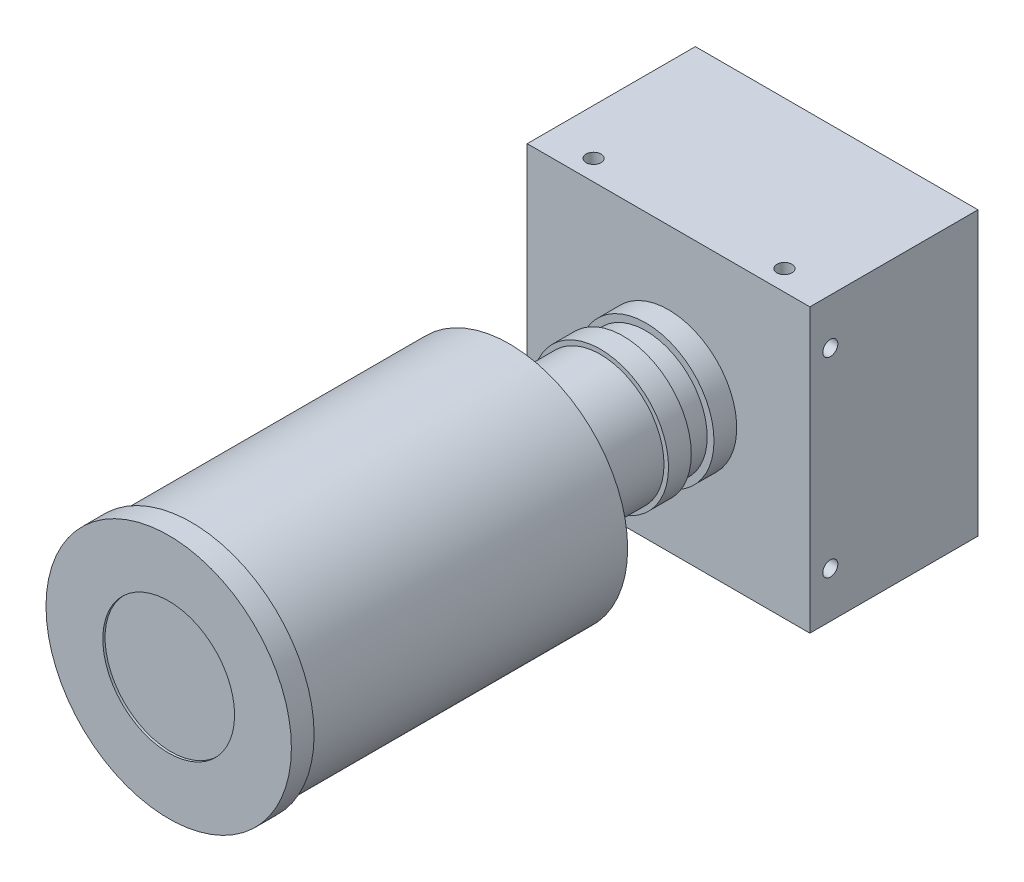
SolidWorks part; units mm, degrees
material "铝合金 (2)"
ref_plane "前基準面" through (0, 0, 0) normal (0, 0, 1) x (1, 0, 0)
ref_plane "上基準面" through (0, 0, 0) normal (0, 1, 0) x (1, 0, 0)
ref_plane "右基準面" through (0, 0, 0) normal (1, 0, 0) x (0, 0, -1)
sketch "草图1" plane through (0, 0, 0) normal (0, 0, 1) x (1, 0, 0)
  line L1 (0, 0) -> (62.2, 0)
  line L2 (0, 0) -> (0, 62.2)
  line L3 (0, 62.2) -> (62.2, 62.2)
  line L4 (62.2, 0) -> (62.2, 62.2)
  dimension "D1" = 62.2
extrude "凸台-拉伸1" add sketch "草图1" along normal blind 37
sketch "草图2" plane through (0, 0, 37) normal (0, 0, 1) x (1, 0, 0)
  line L0 (31.1, 62.2) -> (31.1, 0) construction
  line L1 (62.2, 62.2) -> (0, 62.2) construction
  line L2 (0, 0) -> (62.2, 0) construction
  circle A0 centre (31.1, 31.1) radius 15
  dimension "D1" = 30
extrude "凸台-拉伸2" add sketch "草图2" along normal blind 5
sketch "草图3" plane through (0, 0, 42) normal (0, 0, 1) x (1, 0, 0)
  circle A0 centre (31.1, 31.1) radius 13.5
  dimension "D1" = 27
extrude "凸台-拉伸3" add sketch "草图3" along normal blind 5
sketch "草图4" plane through (0, 0, 47) normal (0, 0, 1) x (1, 0, 0)
  circle A0 centre (31.1, 31.1) radius 15
  dimension "D1" = 30
extrude "凸台-拉伸4" add sketch "草图4" along normal blind 5
sketch "草图5" plane through (0, 0, 52) normal (0, 0, 1) x (1, 0, 0)
  circle A0 centre (31.1, 31.1) radius 14
  dimension "D1" = 28
extrude "凸台-拉伸5" add sketch "草图5" along normal blind 20
sketch "草图6" plane through (0, 0, 72) normal (0, 0, 1) x (1, 0, 0)
  circle A0 centre (31.1, 31.1) radius 26
  dimension "D1" = 52
extrude "凸台-拉伸6" add sketch "草图6" along normal blind 70
sketch "草图7" plane through (0, 0, 142) normal (0, 0, 1) x (1, 0, 0)
  circle A0 centre (31.1, 31.1) radius 27
  dimension "D1" = 54
extrude "凸台-拉伸7" add sketch "草图7" along normal blind 5
sketch "草图8" plane through (0, 0, 147) normal (0, 0, 1) x (1, 0, 0)
  circle A0 centre (31.1, 31.1) radius 14.5
  dimension "D1" = 29
extrude "切除-拉伸1" cut sketch "草图8" against normal blind 0.5
sketch "草图9" plane through (0, 0, 0) normal (0, 0, -1) x (-1, 0, 0)
  circle A0 centre (-16.5763, 47.3033) radius 3.4696
  circle A1 centre (-16.5763, 47.3033) radius 4.9876
extrude "凸台-拉伸8" add sketch "草图9" along normal blind 7
sketch "草图10" plane through (0, 0, 0) normal (0, 0, -1) x (-1, 0, 0)
  line L1 (-24.6285, 18.2507) -> (-16.4054, 18.2507)
  line L2 (-24.6285, 18.2507) -> (-24.6285, 13.1265)
  line L3 (-24.6285, 13.1265) -> (-16.4054, 13.1265)
  line L4 (-16.4054, 18.2507) -> (-16.4054, 13.1265)
extrude "切除-拉伸2" cut sketch "草图10" against normal blind 3
hole_wizard "M4 螺纹孔1" positions "草图12" profile "草图11" tap size "M4" standard "ISO"
sketch "草图12" plane through (0, 62.2, 0) normal (0, 1, 0) x (-1, 0, 0)
  line L0 (-31.1, 37) -> (-31.1, 20.8859) construction
  line L1 (-62.2, 37) -> (0, 37) construction
  point P0 (-10.1, 32.5)
  point P1 (-52.1, 32.5)
  dimension "D1" = 42
  dimension "D2" = 4.5
sketch "草图11" plane through (10.1, 62.2, 32.5) normal (1, 0, 0) x (0, 0, 1)
  line L0 (0, 0) -> (0, 11.0914)
  line L1 (0, 11.0914) -> (1.65, 10.1)
  line L2 (1.65, 10.1) -> (1.65, 0)
  line L5 (1.65, 0) -> (0, 0)
  line L10 (0, 11.0914) -> (-1.65, 10.1) construction
  line L11 (0, -6.35) -> (0, 107.95) construction
  dimension "螺纹孔钻头直径" = 3.3
  dimension "螺纹孔钻头深度" = 10.1
  dimension "导头角度" = 118
cosmetic thread "孔螺蚊线1" parameters "D1"=8, "D2"=4
cosmetic thread "孔螺蚊线2" parameters "D1"=8, "D2"=4
hole_wizard "M4 螺纹孔2" positions "草图14" profile "草图13" tap size "M4" standard "ISO"
sketch "草图14" plane through (62.2, 0, 0) normal (1, 0, 0) x (0, 0, -1)
  line L0 (-37, 31.1) -> (-25.6315, 31.1) construction
  line L1 (-37, 0) -> (-37, 62.2) construction
  point P0 (-32.5, 10.1)
  point P1 (-32.5, 52.1)
  dimension "D1" = 4.5
  dimension "D2" = 42
sketch "草图13" plane through (62.2, 10.1, 32.5) normal (0, 1, 0) x (0, 0, -1)
  line L0 (0, 0) -> (0, 11.0914)
  line L1 (0, 11.0914) -> (1.65, 10.1)
  line L2 (1.65, 10.1) -> (1.65, 0)
  line L5 (1.65, 0) -> (0, 0)
  line L10 (0, 11.0914) -> (-1.65, 10.1) construction
  line L11 (0, -6.35) -> (0, 107.95) construction
  dimension "螺纹孔钻头直径" = 3.3
  dimension "螺纹孔钻头深度" = 10.1
  dimension "导头角度" = 118
cosmetic thread "孔螺蚊线3" parameters "D1"=8, "D2"=4
cosmetic thread "孔螺蚊线4" parameters "D1"=8, "D2"=4
hole_wizard "M4 螺纹孔3" positions "草图16" profile "草图15" tap size "M4" standard "ISO"
sketch "草图16" plane through (0, 0, 0) normal (0, -1, 0) x (1, 0, 0)
  line L0 (31.1, 37) -> (31.1, 26.6089) construction
  line L1 (0, 37) -> (62.2, 37) construction
  point P0 (10.1, 32.5)
  point P1 (52.1, 32.5)
  dimension "D1" = 42
  dimension "D2" = 4.5
sketch "草图15" plane through (10.1, 0, 32.5) normal (1, 0, 0) x (0, 0, -1)
  line L0 (0, 0) -> (0, 11.0914)
  line L1 (0, 11.0914) -> (1.65, 10.1)
  line L2 (1.65, 10.1) -> (1.65, 0)
  line L5 (1.65, 0) -> (0, 0)
  line L10 (0, 11.0914) -> (-1.65, 10.1) construction
  line L11 (0, -6.35) -> (0, 107.95) construction
  dimension "螺纹孔钻头直径" = 3.3
  dimension "螺纹孔钻头深度" = 10.1
  dimension "导头角度" = 118
cosmetic thread "孔螺蚊线5" parameters "D1"=8, "D2"=4
cosmetic thread "孔螺蚊线6" parameters "D1"=8, "D2"=4
hole_wizard "M4 螺纹孔4" positions "草图18" profile "草图17" tap size "M4" standard "ISO"
sketch "草图18" plane through (0, 0, 0) normal (-1, 0, 0) x (0, 0, 1)
  line L0 (37, 31.1) -> (21.3784, 31.1) construction
  line L1 (37, 62.2) -> (37, 0) construction
  point P0 (32.5, 52.1)
  point P1 (32.5, 10.1)
  dimension "D1" = 4.5
  dimension "D2" = 42
sketch "草图17" plane through (0, 52.1, 32.5) normal (0, 1, 0) x (0, 0, 1)
  line L0 (0, 0) -> (0, 11.0914)
  line L1 (0, 11.0914) -> (1.65, 10.1)
  line L2 (1.65, 10.1) -> (1.65, 0)
  line L5 (1.65, 0) -> (0, 0)
  line L10 (0, 11.0914) -> (-1.65, 10.1) construction
  line L11 (0, -6.35) -> (0, 107.95) construction
  dimension "螺纹孔钻头直径" = 3.3
  dimension "螺纹孔钻头深度" = 10.1
  dimension "导头角度" = 118
cosmetic thread "孔螺蚊线7" parameters "D1"=8, "D2"=4
cosmetic thread "孔螺蚊线8" parameters "D1"=8, "D2"=4
